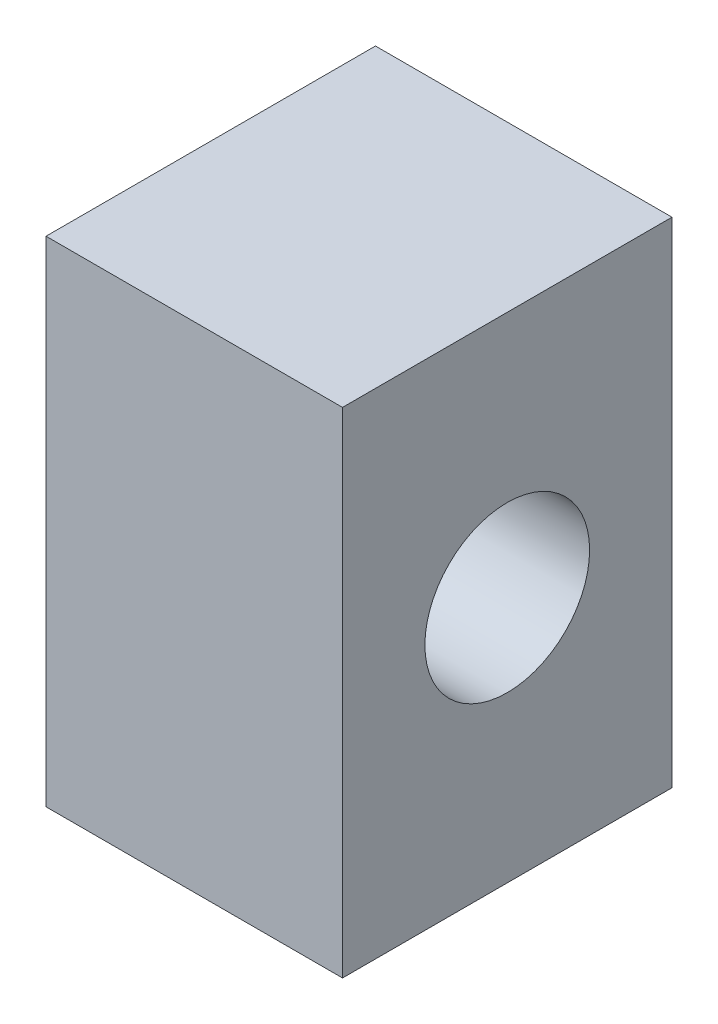
SolidWorks part; units mm, degrees
ref_plane "Front Plane" through (0, 0, 0) normal (0, 0, 1) x (1, 0, 0)
ref_plane "Top Plane" through (0, 0, 0) normal (0, 1, 0) x (1, 0, 0)
ref_plane "Right Plane" through (0, 0, 0) normal (1, 0, 0) x (0, 0, -1)
sketch "Sketch1" plane through (0, 0, 0) normal (0, 1, 0) x (1, 0, 0)
  line L1 (-11.43, -12.7) -> (11.43, -12.7)
  line L2 (-11.43, -12.7) -> (-11.43, 12.7)
  line L3 (-11.43, 12.7) -> (11.43, 12.7)
  line L4 (11.43, -12.7) -> (11.43, 12.7)
  line L5 (-11.43, -12.7) -> (11.43, 12.7) construction
  line L6 (-11.43, 12.7) -> (11.43, -12.7) construction
  point P0 (0, 0)
  dimension "D1" = 22.86
  dimension "D2" = 25.4
extrude "Boss-Extrude1" add sketch "Sketch1" along normal blind 38.1
sketch "Sketch2" plane through (11.43, 0, 0) normal (1, 0, 0) x (0, 0, -1)
  line L1 (-12.7, 38.1) -> (12.7, 38.1)
  line L2 (-12.7, 38.1) -> (-12.7, 0)
  line L3 (-12.7, 0) -> (12.7, 0)
  line L4 (12.7, 38.1) -> (12.7, 0)
  line L5 (-12.7, 38.1) -> (12.7, 0) construction
  line L6 (-12.7, 0) -> (12.7, 38.1) construction
  circle A0 centre (0, 19.05) radius 6.35
  point P4 (0, 19.05)
  dimension "D1" = 12.7
extrude "Cut-Extrude1" cut sketch "Sketch2" against normal through all contours A0
equation "\"handle_angle\" = 15deg"
equation "\"handle_length\"= 24in"
equation "\"handle_dia\"= 1.5in"
equation "\"handle_thickness\"= 0.25in"
equation "\"handle_inner_dia\"= \"handle_dia\" - 2 * \"handle_thickness\""
equation "\"collar_height\"= 1.5in"
equation "\"collar_thickness\"= 0.5"
equation "\"collar_inner_width\"= 1in"
equation "\"bolt_dia\"= 0.5in"
equation "\"D1@Sketch1\"=\"collar_inner_width\"*0.9"
equation "\"D1@Boss-Extrude1\"=\"collar_height\""
equation "\"D1@Sketch2\"=\"bolt_dia\""
